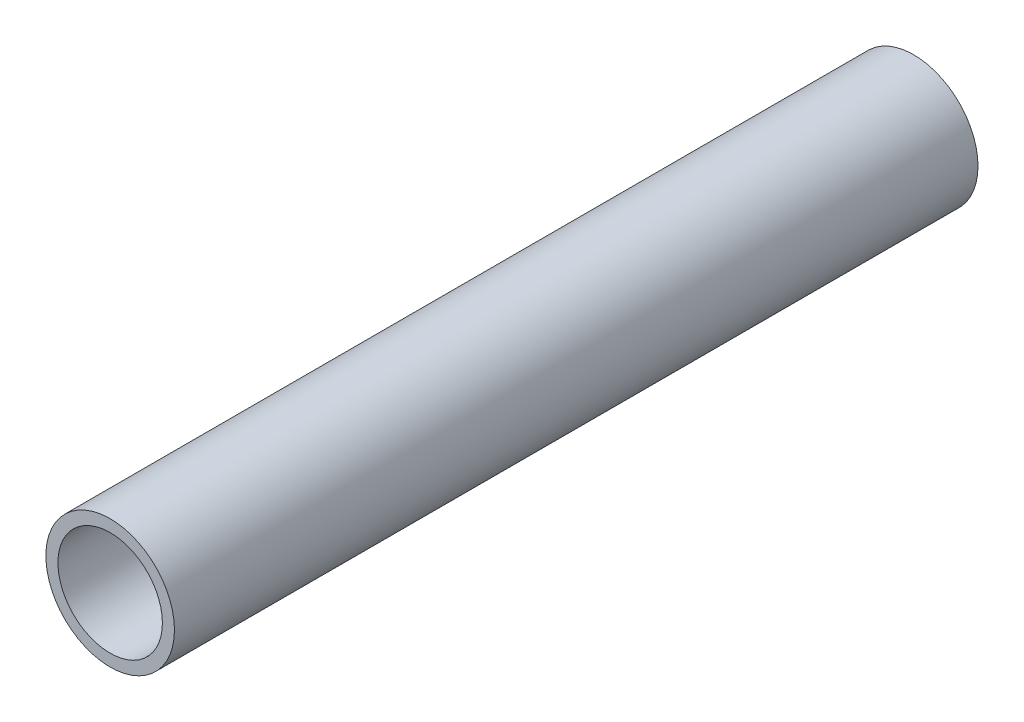
SolidWorks part; units mm, degrees
material "AISI 316 Annealed Stainless Steel Bar (SS)"
ref_plane "Front Plane" through (0, 0, 0) normal (0, 0, 1) x (1, 0, 0)
ref_plane "Top Plane" through (0, 0, 0) normal (0, 1, 0) x (1, 0, 0)
ref_plane "Right Plane" through (0, 0, 0) normal (1, 0, 0) x (0, 0, -1)
sketch "Sketch1" plane through (0, 0, 0) normal (0, 0, 1) x (1, 0, 0)
  circle A0 centre (0, 0) radius 6.4
  circle A1 centre (0, 0) radius 5.2
  dimension "D1" = 12.8
  dimension "D2" = 10.4
extrude "Boss-Extrude1" add sketch "Sketch1" along normal blind 80
